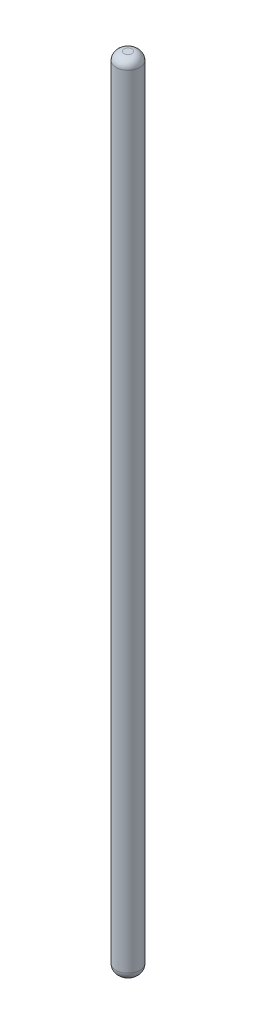
SolidWorks part; units mm, degrees
ref_plane "Front Plane" through (0, 0, 0) normal (0, 0, 1) x (1, 0, 0)
ref_plane "Top Plane" through (0, 0, 0) normal (0, 1, 0) x (1, 0, 0)
ref_plane "Right Plane" through (0, 0, 0) normal (1, 0, 0) x (0, 0, -1)
sketch "Sketch1" plane through (0, 0, 0) normal (0, 1, 0) x (1, 0, 0)
  circle A0 centre (0, 0) radius 1.5
  dimension "D1" = 3
extrude "Boss-Extrude1" add sketch "Sketch1" along normal blind 100
fillet "Fillet1" radius 1 2 edges at (0, 0, 1.5) (0, 100, 1.5)
